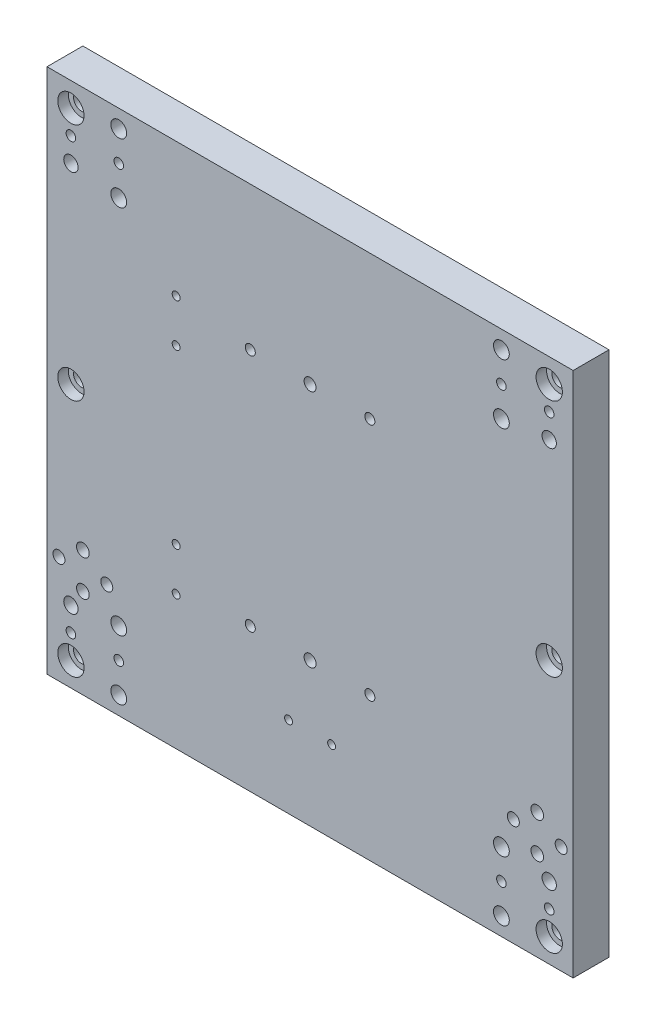
SolidWorks part; units mm, degrees
ref_plane "Front Plane" through (0, 0, 0) normal (0, 0, 1) x (1, 0, 0)
ref_plane "Top Plane" through (0, 0, 0) normal (0, 1, 0) x (1, 0, 0)
ref_plane "Right Plane" through (0, 0, 0) normal (1, 0, 0) x (0, 0, -1)
ref_plane "Ebene1" through (0, 0, 0) normal (0, 0, -1) x (-1, 0, 0)
sketch "Skizze1" plane through (0, 0, 0) normal (0, 0, -1) x (-1, 0, 0)
  line L0 (110, 110) -> (-110, 110)
  line L1 (-110, 110) -> (-110, -110)
  line L2 (-110, -110) -> (110, -110)
  line L3 (110, -110) -> (110, 110)
extrude "Aufsatz-Linear austragen1" add sketch "Skizze1" against normal blind 15
hole_wizard "Ø6.0mm Stiftloch1" positions "Skizze3" profile "Skizze2" hole size "Ø6.0" standard "DIN" end condition through all
sketch "Skizze3" plane through (0, 0, 0) normal (0, 0, -1) x (-1, 0, 0)
  line L0 (-110, 0) -> (110, 0) construction
  line L1 (-110, 110) -> (-110, -110) construction
  line L2 (110, -110) -> (110, 110) construction
  line L5 (0, 110) -> (0, -110) construction
  line L6 (110, 110) -> (-110, 110) construction
  line L7 (-110, -110) -> (110, -110) construction
  point P0 (-100, -80)
  point P1 (-100, 80)
  point P2 (100, 80)
  point P3 (100, -80)
  dimension "D1" = 160
  dimension "D2" = 200
sketch "Skizze2" plane through (100, -80, 0) normal (1, 0, 0) x (0, 1, 0)
  line L0 (0, 0) -> (0, 15)
  line L1 (0, 15) -> (3, 15)
  line L2 (3, 15) -> (3, 0)
  line L5 (3, 0) -> (0, 0)
  line L11 (0, -6.35) -> (0, 107.95) construction
  dimension "Bohrerdurchmesser" = 6
  dimension "Bohrungstiefe" = 15
hole_wizard "Ø5.0mm Stiftloch1" positions "Skizze5" profile "Skizze4" hole size "Ø5.0" standard "DIN" end condition through all
sketch "Skizze5" plane through (0, 0, 0) normal (0, 0, -1) x (-1, 0, 0)
  line L0 (0, 110) -> (0, -110) construction
  line L1 (110, 110) -> (-110, 110) construction
  line L2 (-110, -110) -> (110, -110) construction
  line L4 (110, 0) -> (-110, 0) construction
  line L5 (110, -110) -> (110, 110) construction
  line L6 (-110, 110) -> (-110, -110) construction
  point P0 (0, 50)
  point P1 (0, -50)
  point P2 (105, -65)
  point P3 (85, -65)
  point P4 (-85, -65)
  point P5 (-105, -65)
  dimension "D1" = 100
sketch "Skizze4" plane through (0, 50, 0) normal (1, 0, 0) x (0, 1, 0)
  line L0 (0, 0) -> (0, 15)
  line L1 (0, 15) -> (2.5, 15)
  line L2 (2.5, 15) -> (2.5, 0)
  line L5 (2.5, 0) -> (0, 0)
  line L11 (0, -6.35) -> (0, 107.95) construction
  dimension "Bohrerdurchmesser" = 5
  dimension "Bohrungstiefe" = 15
hole_wizard "M5 Gewindebohrung1" positions "Skizze7" profile "Skizze6" tap size "M5" standard "DIN" end condition through all
sketch "Skizze7" plane through (0, 0, 15) normal (0, 0, 1) x (1, 0, 0)
  line L0 (0, 110) -> (0, -110)
  line L1 (-110, 110) -> (110, 110) construction
  line L2 (110, -110) -> (-110, -110) construction
  line L5 (110, 0) -> (-110, 0) construction
  line L6 (110, 110) -> (110, -110) construction
  line L7 (-110, -110) -> (-110, 110) construction
  point P0 (-25, 50)
  point P1 (25, 50)
  point P2 (25, -50)
  point P3 (-25, -50)
  dimension "D1" = 100
  dimension "D2" = 50
sketch "Skizze6" plane through (-25, 50, 15) normal (1, 0, 0) x (0, -1, 0)
  line L0 (0, 0) -> (0, 15)
  line L1 (0, 15) -> (2.1, 15)
  line L2 (2.1, 15) -> (2.1, 0)
  line L5 (2.1, 0) -> (0, 0)
  line L11 (0, -6.35) -> (0, 107.95) construction
  dimension "Nenndurchmesser (Haupt)" = 4.2
  dimension "Bohrungstiefe" = 15
hole_wizard "Stirnsenkung für M6 Zylinderschraube mit Innensechskant1" positions "Skizze11" profile "Skizze10" counterbore size "M6" standard "DIN" end condition through all
sketch "Skizze11" plane through (0, 0, 15) normal (0, 0, 1) x (1, 0, 0)
  line L0 (-110, 0) -> (110, 0) construction
  line L1 (-110, -110) -> (-110, 110) construction
  line L2 (110, 110) -> (110, -110) construction
  line L5 (0, 110) -> (0, -110) construction
  line L6 (-110, 110) -> (110, 110) construction
  line L7 (110, -110) -> (-110, -110) construction
  line L9 (-100, 110) -> (-100, -110) construction
  line L11 (100, 110) -> (100, -110) construction
  point P0 (100, -100)
  point P1 (100, 0)
  point P2 (-100, -100)
  point P3 (-100, 0)
  point P4 (-100, 100)
  point P5 (100, 100)
  dimension "D1" = 200
  dimension "D2" = 200
sketch "Skizze10" plane through (100, -100, 15) normal (1, 0, 0) x (0, -1, 0)
  line L0 (0, 0) -> (0, 15)
  line L1 (0, 15) -> (3.3, 15)
  line L3 (3.3, 15) -> (3.3, 4.4)
  line L4 (3.3, 4.4) -> (5.5, 4.4)
  line L5 (5.5, 4.4) -> (5.5, 0)
  line L7 (5.5, 0) -> (0, 0)
  line L11 (0, -6.35) -> (0, 107.95) construction
  dimension "Bohrerdurchmesser" = 6.6
  dimension "Bohrungstiefe" = 15
  dimension "Senkdurchmesser2" = 11
  dimension "Senktiefe2" = 4.4
hole_wizard "M4 Gewindebohrung1" positions "Skizze13" profile "Skizze12" tap size "M4" standard "DIN"
sketch "Skizze13" plane through (0, 0, 15) normal (0, 0, 1) x (1, 0, 0)
  line L0 (-56, 110) -> (-56, -110) construction
  line L1 (-110, 110) -> (110, 110) construction
  line L2 (110, -110) -> (-110, -110) construction
  line L4 (0, 110) -> (0, -110) construction
  line L6 (-110, 0) -> (110, 0) construction
  line L7 (-110, -110) -> (-110, 110) construction
  line L8 (110, 110) -> (110, -110) construction
  line L10 (-9, -76) -> (9, -76) construction
  point P0 (-56, 54)
  point P1 (-56, 36)
  point P2 (-56, -36)
  point P3 (-56, -54)
  point P4 (9, -76)
  point P5 (-9, -76)
  dimension "D1" = 18
  dimension "D2" = 18
  dimension "D3" = 18
  dimension "D4" = 76
  dimension "D5" = 72
  dimension "D6" = 56
sketch "Skizze12" plane through (-56, 54, 15) normal (1, 0, 0) x (0, -1, 0)
  line L0 (0, 0) -> (0, 12.4914)
  line L1 (0, 12.4914) -> (1.65, 11.5)
  line L2 (1.65, 11.5) -> (1.65, 0)
  line L5 (1.65, 0) -> (0, 0)
  line L10 (0, 12.4914) -> (-1.65, 11.5) construction
  line L11 (0, -6.35) -> (0, 107.95) construction
  dimension "Bohrerdurchmesser" = 3.3
  dimension "Bohrungstiefe" = 11.5
  dimension "Spitzenwinkel" = 118
hole_wizard "Stirnsenkung für M5 Sechskantschraube mit Schaft1" positions "Skizze15" profile "Skizze14" counterbore size "M5" standard "ANSI Metrisch"
sketch "Skizze15" plane through (0, 0, 0) normal (0, 0, -1) x (-1, 0, 0)
  point P0 (95, -57.5)
  point P1 (95, -72.5)
  point P2 (-95, -57.5)
  point P3 (-95, -72.5)
sketch "Skizze14" plane through (-95, -57.5, 0) normal (1, 0, 0) x (0, 1, 0)
  line L0 (0, 0) -> (0, 15)
  line L1 (0, 15) -> (2.65, 15)
  line L3 (2.65, 15) -> (2.65, 5.4)
  line L4 (2.65, 5.4) -> (5, 5.4)
  line L5 (5, 5.4) -> (5, 0)
  line L7 (5, 0) -> (0, 0)
  line L11 (0, -6.35) -> (0, 107.95) construction
  dimension "Bohrerdurchmesser" = 5.3
  dimension "Bohrungstiefe" = 15
  dimension "Senkdurchmesser2" = 10
  dimension "Senktiefe2" = 5.4
hole_wizard "Stirnsenkung für M6 Zylinderschraube mit Innensechskant2" positions "Skizze17" profile "Skizze18" counterbore size "M6" standard "DIN" end condition through all
sketch "Skizze17" plane through (0, 0, 0) normal (0, 0, -1) x (-1, 0, 0)
  line L0 (-80, 102.5) -> (-80, 77.5) construction
  line L3 (0, 110) -> (0, -110) construction
  line L4 (110, 110) -> (-110, 110) construction
  line L5 (-110, -110) -> (110, -110) construction
  line L8 (-110, 0) -> (110, 0) construction
  line L9 (-110, 110) -> (-110, -110) construction
  line L10 (110, -110) -> (110, 110) construction
  point P0 (-80, 102.5)
  point P2 (-80, 77.5)
  point P28 (80, 77.5)
  point P29 (80, 102.5)
  point P31 (80, -77.5)
  point P32 (80, -102.5)
  point P33 (-80, -77.5)
  point P34 (-80, -102.5)
  dimension "D1" = 25
  dimension "D2" = 30
  dimension "D3" = 7.5
sketch "Skizze18" plane through (80, 102.5, 0) normal (1, 0, 0) x (0, 1, 0)
  line L0 (0, 0) -> (0, 15)
  line L1 (0, 15) -> (3.3, 15)
  line L3 (3.3, 15) -> (3.3, 4.4)
  line L4 (3.3, 4.4) -> (5.5, 4.4)
  line L5 (5.5, 4.4) -> (5.5, 0)
  line L7 (5.5, 0) -> (0, 0)
  line L11 (0, -6.35) -> (0, 107.95) construction
  dimension "Bohrerdurchmesser" = 6.6
  dimension "Bohrungstiefe" = 15
  dimension "Senkdurchmesser2" = 11
  dimension "Senktiefe2" = 4.4
hole_wizard "Ø4.0mm Stiftloch1" positions "Skizze19" profile "Skizze20" hole size "Ø4.0" standard "DIN" end condition through all
sketch "Skizze19" plane through (0, 0, 0) normal (0, 0, -1) x (-1, 0, 0)
  line L0 (0, 110) -> (0, -110) construction
  line L1 (110, 110) -> (-110, 110) construction
  line L2 (-110, -110) -> (110, -110) construction
  line L5 (110, 0) -> (-110, 0) construction
  line L6 (110, -110) -> (110, 110) construction
  line L7 (-110, 110) -> (-110, -110) construction
  line L10 (-80, 90) -> (-100, 90) construction
  point P0 (-100, 90)
  point P2 (-80, 90)
  point P30 (80, 90)
  point P31 (100, 90)
  point P32 (100, -90)
  point P33 (80, -90)
  point P34 (-80, -90)
  point P35 (-100, -90)
  dimension "D1" = 20
  dimension "D2" = 10
  dimension "D3" = 20
sketch "Skizze20" plane through (100, 90, 0) normal (1, 0, 0) x (0, 1, 0)
  line L0 (0, 0) -> (0, 15)
  line L1 (0, 15) -> (2, 15)
  line L2 (2, 15) -> (2, 0)
  line L5 (2, 0) -> (0, 0)
  line L11 (0, -6.35) -> (0, 107.95) construction
  dimension "Bohrerdurchmesser" = 4
  dimension "Bohrungstiefe" = 15
